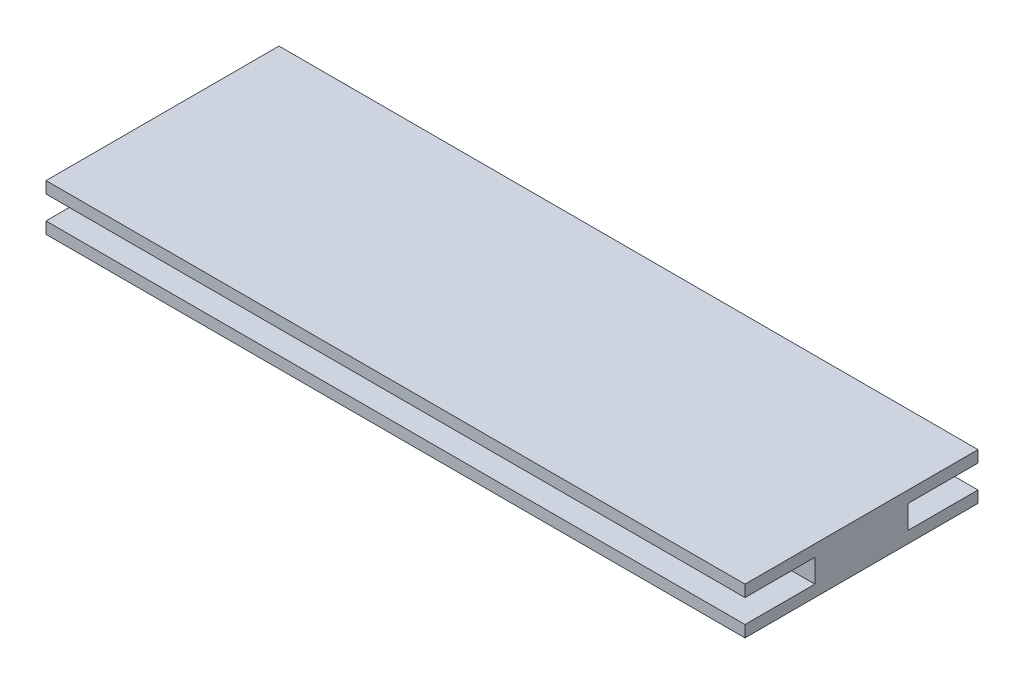
SolidWorks part; units mm, degrees
ref_plane "Front Plane" through (0, 0, 0) normal (0, 0, 1) x (1, 0, 0)
ref_plane "Top Plane" through (0, 0, 0) normal (0, 1, 0) x (1, 0, 0)
ref_plane "Right Plane" through (0, 0, 0) normal (1, 0, 0) x (0, 0, -1)
other "Bounding Box"
ref_plane "Default Plane" through (0, 3.175, -15.875) normal (0, 0, 1) x (1, 0, 0)
sketch "Sketch1" plane through (0, 0, 0) normal (1, 0, 0) x (0, 0, -1)
  line L0 (-15.875, 1.5875) -> (-15.875, 3.175)
  line L1 (-15.875, -3.175) -> (15.875, -3.175)
  line L2 (-15.875, -3.175) -> (-15.875, -1.5875)
  line L3 (-15.875, 3.175) -> (15.875, 3.175)
  line L4 (15.875, -3.175) -> (15.875, -1.5875)
  line L5 (-15.875, -3.175) -> (15.875, 3.175) construction
  line L6 (-15.875, 3.175) -> (15.875, -3.175) construction
  line L7 (15.875, 1.5875) -> (15.875, 3.175)
  line L14 (6.35, -1.5875) -> (6.35, 1.5875)
  line L15 (-6.35, -1.5875) -> (-6.35, 1.5875)
  line L16 (6.35, 1.5875) -> (15.875, 1.5875)
  line L17 (-6.35, 1.5875) -> (-15.875, 1.5875)
  line L18 (-6.35, -1.5875) -> (-15.875, -1.5875)
  line L19 (6.35, -1.5875) -> (15.875, -1.5875)
  point P0 (0, 0)
  dimension "D1" = 31.75
  dimension "D2" = 6.35
  dimension "D7" = 3.175
  dimension "D8" = 3.175
extrude "Boss-Extrude1" add sketch "Sketch1" along normal blind 95.25
